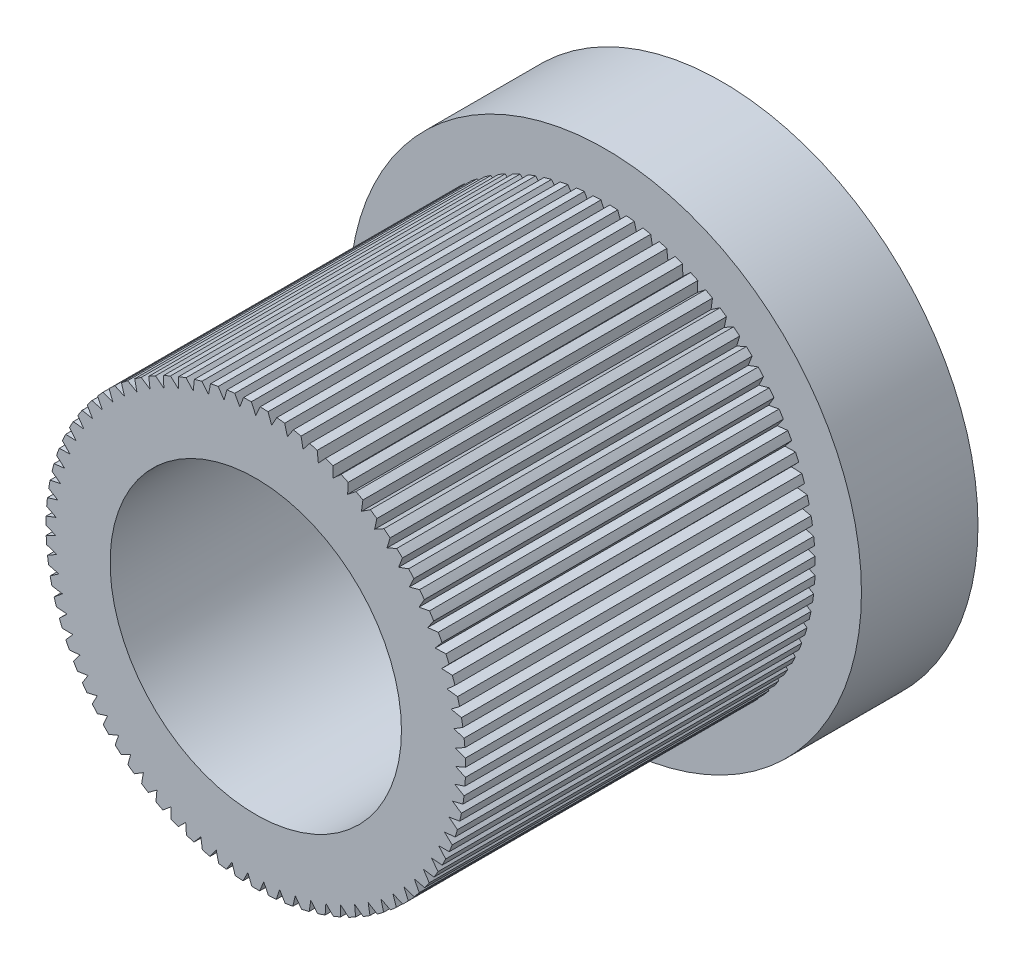
SolidWorks part; units mm, degrees
ref_plane "Ebene vorne" through (0, 0, 0) normal (0, 0, 1) x (1, 0, 0)
ref_plane "Ebene oben" through (0, 0, 0) normal (0, 1, 0) x (1, 0, 0)
ref_plane "Ebene rechts" through (0, 0, 0) normal (1, 0, 0) x (0, 0, -1)
sketch "Skizze1" plane through (0, 0, 0) normal (0, 0, 1) x (1, 0, 0)
  circle A0 centre (0, 0) radius 2.5
  circle A1 centre (0, 0) radius 3.6
  dimension "D1" = 5
  dimension "D2" = 7.2
extrude "Aufsatz-Linear austragen1" add sketch "Skizze1" along normal blind 8
sketch "Skizze2" plane through (0, 0, 0) normal (0, 0, -1) x (-1, 0, 0)
  line L0 (0, 0) -> (0, 3.6) construction
  line L1 (0, 3.4329) -> (-0.0756, 3.5992)
  line L2 (-0.0756, 3.5992) -> (0.0756, 3.5992) construction
  line L3 (0.0756, 3.5992) -> (0, 3.4329)
  circle A0 centre (0, 0) radius 3.6 construction
  arc A1 (-0.0756, 3.5992) -> (0.0756, 3.5992) centre (0, 3.5236) cw
extrude "Schnitt-Linear austragen2" cut sketch "Skizze2" against normal blind 9
pattern_circular "Kreismuster1" count 79 over 360 about axis through (0, 0, 0) along (0, 0, 1) of "Schnitt-Linear austragen2"
sketch "Skizze3" plane through (0, 0, 0) normal (0, 0, -1) x (-1, 0, 0)
  circle A0 centre (0, 0) radius 4.3945
  circle A1 centre (0, 0) radius 2.5 construction
  circle A2 centre (0, 0) radius 2.5
extrude "Aufsatz-Linear austragen2" add sketch "Skizze3" against normal blind 2
